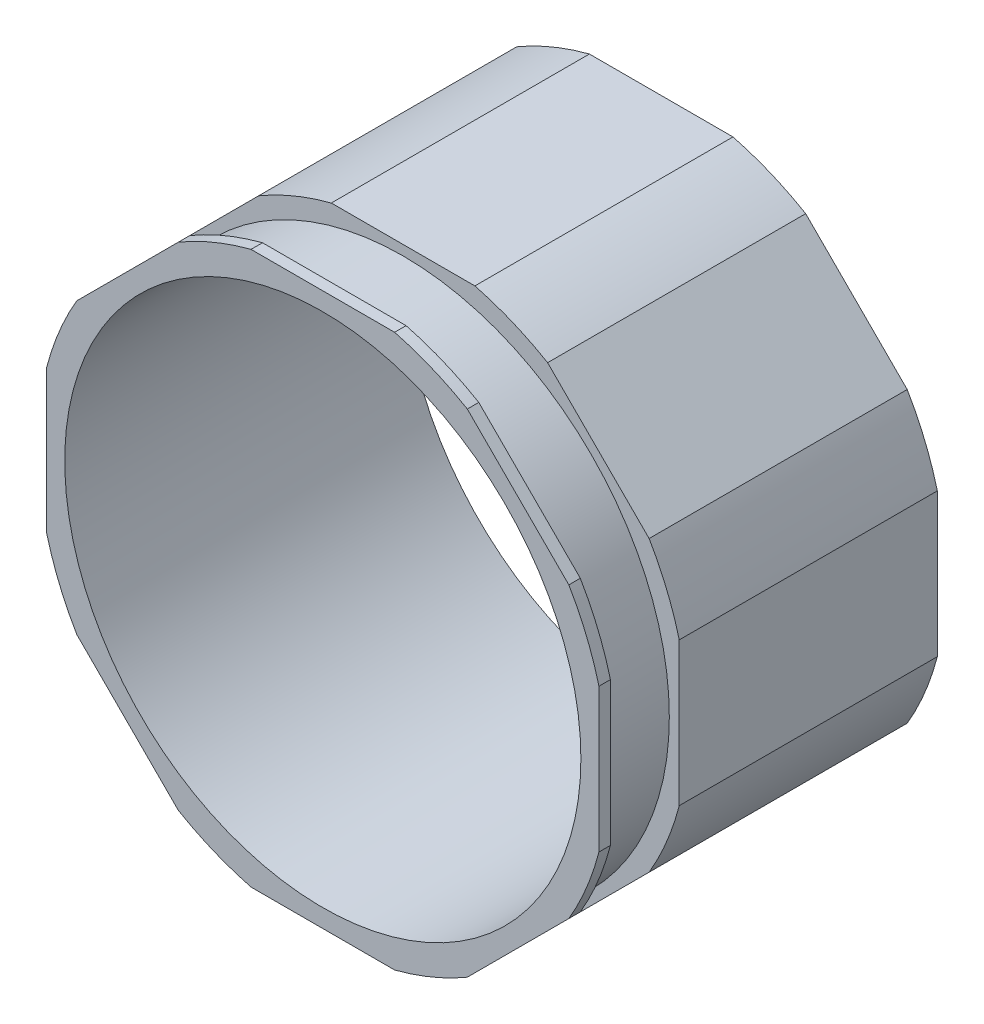
SolidWorks part; units mm, degrees
ref_plane "Front Plane" through (0, 0, 0) normal (0, 0, 1) x (1, 0, 0)
ref_plane "Top Plane" through (0, 0, 0) normal (0, 1, 0) x (1, 0, 0)
ref_plane "Right Plane" through (0, 0, 0) normal (1, 0, 0) x (0, 0, -1)
sketch "Sketch1" plane through (0, 0, 0) normal (0, 0, 1) x (1, 0, 0)
  line L1 (-50.6583, 122.3) -> (-122.3, 50.6583)
  line L2 (-122.3, 50.6583) -> (-122.3, -50.6583)
  line L3 (-122.3, -50.6583) -> (-50.6583, -122.3)
  line L4 (-50.6583, -122.3) -> (50.6583, -122.3)
  line L5 (50.6583, -122.3) -> (122.3, -50.6583)
  line L6 (122.3, -50.6583) -> (122.3, 50.6583)
  line L7 (122.3, 50.6583) -> (50.6583, 122.3)
  line L8 (50.6583, 122.3) -> (-50.6583, 122.3)
  circle A0 centre (0, 0) radius 122.3 construction
  circle A1 centre (0, 0) radius 126.365
  circle A2 centre (0, 0) radius 114.3
  dimension "D2" = 252.73
  dimension "D3" = 228.6
  dimension "D1" = 244.6
extrude "Boss-Extrude1" add sketch "Sketch1" along normal blind 114.3 contours L6 A1 L7 L8 L1 L2 L3 L4 L5 A2 | A2
sketch "Sketch2" plane through (0, 0, 114.3) normal (0, 0, 1) x (1, 0, 0)
  circle A0 centre (0, 0) radius 117.9068
  arc A1 (63.9978, 108.9605) -> (31.7934, 122.3) centre (0, 0) ccw construction
  circle A2 centre (0, 0) radius 114.3
  dimension "D1" = 8.4582
  dimension "D2" = 228.6
extrude "Boss-Extrude2" add sketch "Sketch2" along normal blind 30.48 contours A2 | A0
sketch "Sketch3" plane through (0, 0, 144.78) normal (0, 0, 1) x (1, 0, 0)
  line L8 (122.3, -31.7934) -> (122.3, 31.7934)
  line L9 (108.9605, 63.9978) -> (63.9978, 108.9605)
  line L10 (31.7934, 122.3) -> (-31.7934, 122.3)
  line L11 (-63.9978, 108.9605) -> (-108.9605, 63.9978)
  line L12 (-122.3, 31.7934) -> (-122.3, -31.7934)
  line L13 (-108.9605, -63.9978) -> (-63.9978, -108.9605)
  line L14 (-31.7934, -122.3) -> (31.7934, -122.3)
  line L15 (63.9978, -108.9605) -> (108.9605, -63.9978)
  line L16 (122.3, -31.7934) -> (122.3, 31.7934)
  line L17 (108.9605, 63.9978) -> (63.9978, 108.9605)
  line L18 (31.7934, 122.3) -> (-31.7934, 122.3)
  line L19 (-63.9978, 108.9605) -> (-108.9605, 63.9978)
  line L20 (-122.3, 31.7934) -> (-122.3, -31.7934)
  line L21 (-108.9605, -63.9978) -> (-63.9978, -108.9605)
  line L22 (-31.7934, -122.3) -> (31.7934, -122.3)
  line L23 (63.9978, -108.9605) -> (108.9605, -63.9978)
  circle A0 centre (0, 0) radius 114.3 construction
  circle A1 centre (0, 0) radius 114.3
  arc A9 (122.3, 31.7934) -> (108.9605, 63.9978) centre (0, 0) ccw
  arc A10 (63.9978, 108.9605) -> (31.7934, 122.3) centre (0, 0) ccw
  arc A11 (-31.7934, 122.3) -> (-63.9978, 108.9605) centre (0, 0) ccw
  arc A12 (-108.9605, 63.9978) -> (-122.3, 31.7934) centre (0, 0) ccw
  arc A13 (-122.3, -31.7934) -> (-108.9605, -63.9978) centre (0, 0) ccw
  arc A14 (-63.9978, -108.9605) -> (-31.7934, -122.3) centre (0, 0) ccw
  arc A15 (31.7934, -122.3) -> (63.9978, -108.9605) centre (0, 0) ccw
  arc A16 (108.9605, -63.9978) -> (122.3, -31.7934) centre (0, 0) ccw
  arc A17 (122.3, 31.7934) -> (108.9605, 63.9978) centre (0, 0) ccw
  arc A18 (63.9978, 108.9605) -> (31.7934, 122.3) centre (0, 0) ccw
  arc A19 (-31.7934, 122.3) -> (-63.9978, 108.9605) centre (0, 0) ccw
  arc A20 (-108.9605, 63.9978) -> (-122.3, 31.7934) centre (0, 0) ccw
  arc A21 (-122.3, -31.7934) -> (-108.9605, -63.9978) centre (0, 0) ccw
  arc A22 (-63.9978, -108.9605) -> (-31.7934, -122.3) centre (0, 0) ccw
  arc A23 (31.7934, -122.3) -> (63.9978, -108.9605) centre (0, 0) ccw
  arc A24 (108.9605, -63.9978) -> (122.3, -31.7934) centre (0, 0) ccw
  circle M2 centre (0, 0) radius 114.3
  circle M3 centre (0, 0) radius 117.9068
  dimension "D1" = 0
extrude "Boss-Extrude3" add sketch "Sketch3" along normal blind 5.08 contours L23 A24 L16 A17 L17 A18 L18 A19 L19 A20 L20 A21 L21 A22 L22 A23 M3 | M2 | M3 M2 | A1
sketch "Sketch5" plane through (0, 0, 149.86) normal (0, 0, 1) x (1, 0, 0)
  text T0 "Through holes on this side"
sketch "Sketch6" plane through (0, 0, 0) normal (0, 0, -1) x (-1, 0, 0)
  text T0 "Threaded holes on this side"
